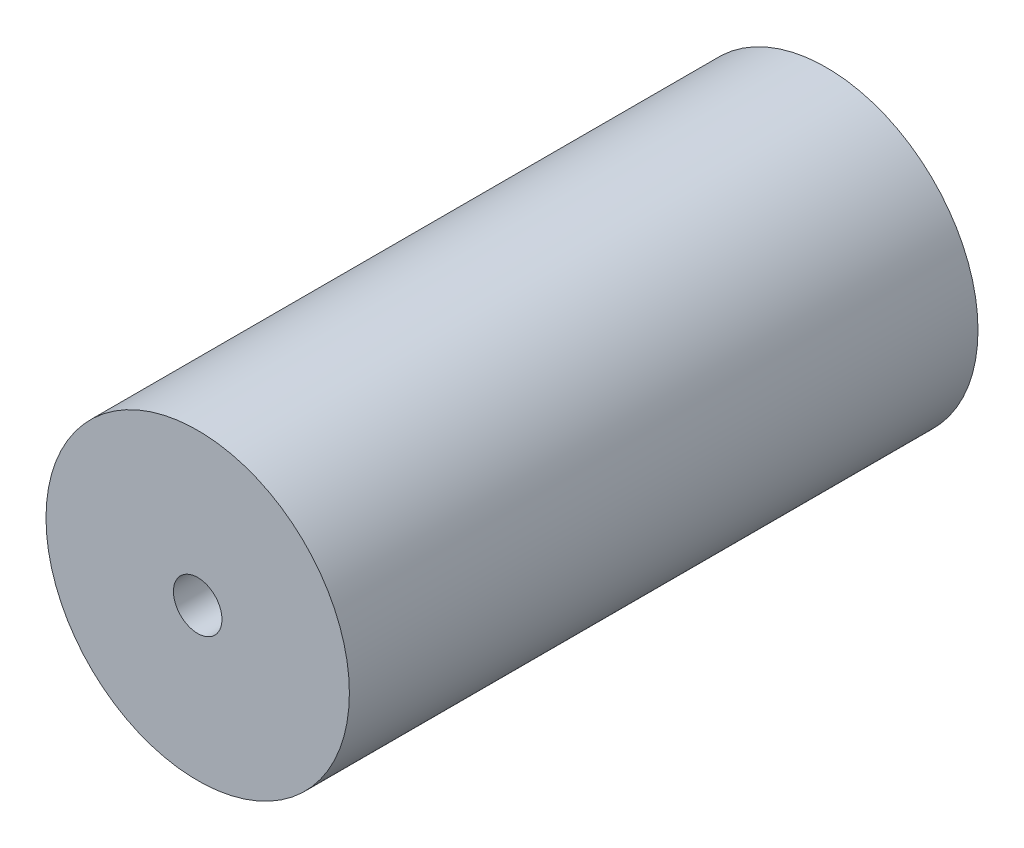
SolidWorks part; units mm, degrees
ref_plane "Front Plane" through (0, 0, 0) normal (0, 0, 1) x (1, 0, 0)
ref_plane "Top Plane" through (0, 0, 0) normal (0, 1, 0) x (1, 0, 0)
ref_plane "Right Plane" through (0, 0, 0) normal (1, 0, 0) x (0, 0, -1)
sketch "Sketch1" plane through (0, 0, 0) normal (0, 0, 1) x (1, 0, 0)
  circle A0 centre (0, 0) radius 12.5
  dimension "D1" = 25
extrude "Boss-Extrude1" add sketch "Sketch1" along normal blind 51.8
sketch "Sketch2" plane through (0, 0, 0) normal (0, 0, -1) x (-1, 0, 0)
  circle A0 centre (0, 0) radius 3.5
  dimension "D1" = 7
extrude "Boss-Extrude2" add sketch "Sketch2" along normal blind 2.38
sketch "Sketch3" plane through (0, 0, 0) normal (0, 0, -1) x (-1, 0, 0)
  line L0 (0, -12.5) -> (0, 12.5) construction
  circle A0 centre (8.5, 0) radius 1.5
  circle A1 centre (-8.5, 0) radius 1.5
  circle A2 centre (0, 0) radius 12.5 construction
  dimension "D1" = 3
  dimension "D2" = 17
extrude "Cut-Extrude1" cut sketch "Sketch3" against normal blind 5
sketch "Sketch4" plane through (0, 0, -2.38) normal (0, 0, -1) x (-1, 0, 0)
  circle A0 centre (0, 0) radius 2
  dimension "D1" = 4
extrude "Cut-Extrude2" cut sketch "Sketch4" against normal through all
